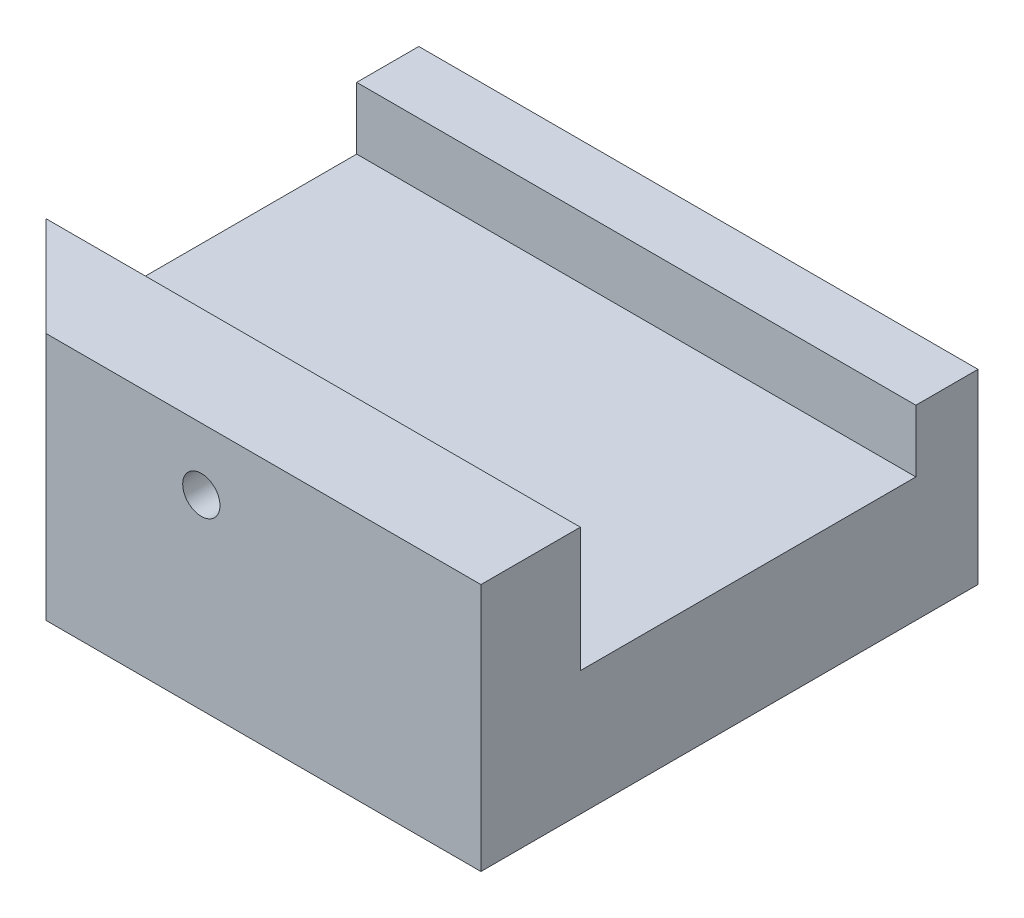
SolidWorks part; units mm, degrees
material "POM 乙缩醛共聚物"
ref_plane "前视基准面" through (0, 0, 0) normal (0, 0, 1) x (1, 0, 0)
ref_plane "上视基准面" through (0, 0, 0) normal (0, 1, 0) x (1, 0, 0)
ref_plane "右视基准面" through (0, 0, 0) normal (1, 0, 0) x (0, 0, -1)
sketch "草图1" plane through (0, 0, 0) normal (0, 1, 0) x (1, 0, 0)
  line L1 (-22.5, -20) -> (22.5, -20)
  line L2 (-22.5, -20) -> (-22.5, 20)
  line L3 (-22.5, 20) -> (22.5, 20)
  line L4 (22.5, -20) -> (22.5, 20)
  line L5 (-22.5, -20) -> (22.5, 20) construction
  line L6 (-22.5, 20) -> (22.5, -20) construction
  point P0 (0, 0)
  dimension "D1" = 45
  dimension "D2" = 40
extrude "凸台-拉伸1" add sketch "草图1" along normal blind 20
sketch "草图2" plane through (0, 0, -20) normal (0, 0, -1) x (-1, 0, 0)
  line L0 (22.5, 20) -> (22.5, 0) construction
  line L1 (-22.5, 20) -> (22.5, 20)
  line L2 (-22.5, 20) -> (-22.5, 10)
  line L3 (-22.5, 10) -> (22.5, 10)
  line L4 (22.5, 20) -> (22.5, 10)
  dimension "D1" = 10
extrude "切除-拉伸1" cut sketch "草图2" against normal blind 32
sketch "草图3" plane through (0, 10, 0) normal (0, 1, 0) x (1, 0, 0)
  line L0 (22.5, -12) -> (22.5, 20) construction
  line L1 (-22.5, 20) -> (22.5, 20)
  line L2 (-22.5, 20) -> (-22.5, 15)
  line L3 (-22.5, 15) -> (22.5, 15)
  line L4 (22.5, 20) -> (22.5, 15)
  dimension "D1" = 5
extrude "凸台-拉伸2" add sketch "草图3" along normal blind 5
sketch "草图4" plane through (0, 0, 12) normal (0, 0, -1) x (-1, 0, 0)
  line L0 (0, 10) -> (0, 20) construction
  line L1 (22.5, 10) -> (-22.5, 10) construction
  line L2 (22.5, 20) -> (-22.5, 20) construction
  circle A0 centre (0, 15) radius 1.5
  dimension "D1" = 3
extrude "切除-拉伸2" cut sketch "草图4" against normal through all
chamfer "倒角1" distance 10 angle 45 1 edges at (-22.5, 10, 20)
